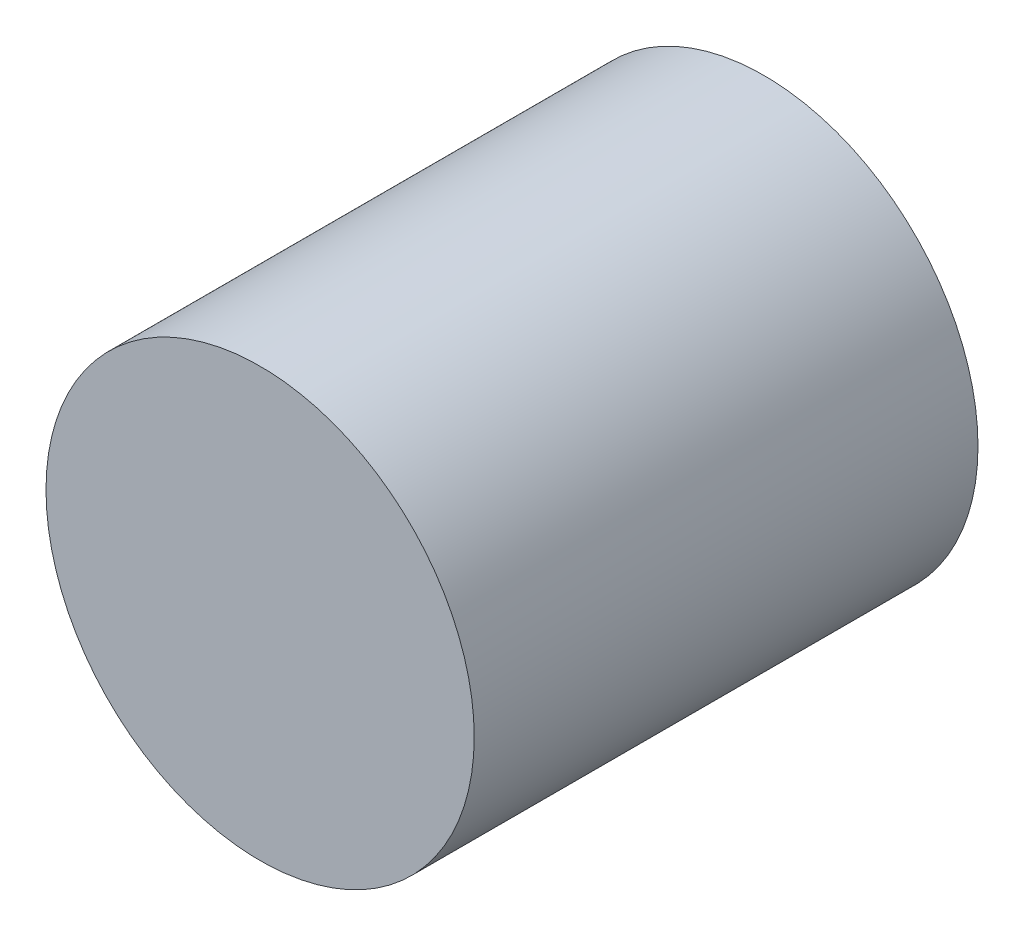
SolidWorks part; units mm, degrees
ref_plane "前视基准面" through (0, 0, 0) normal (0, 0, 1) x (1, 0, 0)
ref_plane "上视基准面" through (0, 0, 0) normal (0, 1, 0) x (1, 0, 0)
ref_plane "右视基准面" through (0, 0, 0) normal (1, 0, 0) x (0, 0, -1)
other "Configuration Table"
sketch "草图1" plane through (0, 0, 0) normal (0, 0, 1) x (1, 0, 0)
  line L0 (-45, 0) -> (45, 0)
  line L1 (45, 0) -> (45, 15)
  line L2 (45, 15) -> (10, 15)
  line L3 (10, 15) -> (10, 90)
  line L4 (10, 90) -> (-10, 90)
  line L5 (-10, 90) -> (-10, 15)
  line L6 (-10, 15) -> (-45, 15)
  line L7 (-45, 15) -> (-45, 0)
extrude "凸台-拉伸1" add sketch "草图1" along normal blind 12
sketch "草图2" plane through (0, 0, 12) normal (0, 0, 1) x (1, 0, 0)
  circle A0 centre (0, 65) radius 5.1
extrude "切除-拉伸1" cut sketch "草图2" against normal through all flip side to cut
